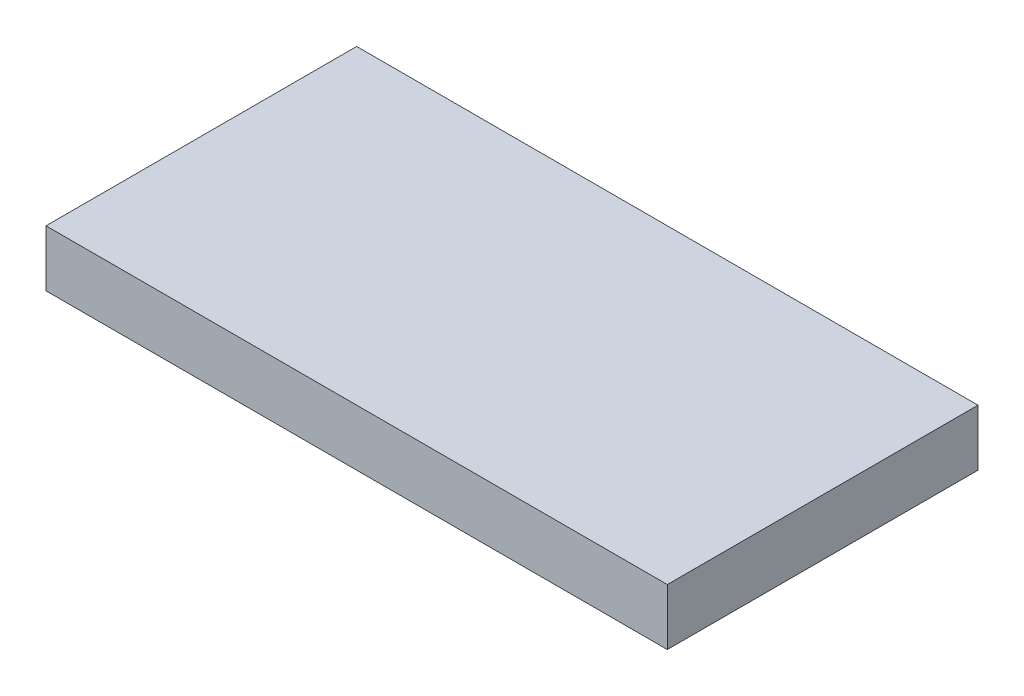
SolidWorks part; units mm, degrees
ref_plane "前视基准面" through (0, 0, 0) normal (0, 0, 1) x (1, 0, 0)
ref_plane "上视基准面" through (0, 0, 0) normal (0, 1, 0) x (1, 0, 0)
ref_plane "右视基准面" through (0, 0, 0) normal (1, 0, 0) x (0, 0, -1)
other "Configuration Table"
sketch "草图1" plane through (0, 0, 0) normal (0, 1, 0) x (1, 0, 0)
  line L0 (0, 0) -> (0, 80)
  line L1 (0, 80) -> (80, 80)
  line L2 (80, 80) -> (80, 0)
  line L3 (80, 0) -> (-80, 0)
  line L4 (-80, 0) -> (-80, 80)
  line L5 (-80, 80) -> (0, 80)
  dimension "D1" = 80
  dimension "D2" = 80
  dimension "D3" = 80
  dimension "D4" = 80
extrude "凸台-拉伸1" add sketch "草图1" along normal blind 14.5
sketch "草图3" plane through (0, 0, 0) normal (0, -1, 0) x (1, 0, 0)
  line L0 (0, 0) -> (0, -15)
  line L1 (0, -15) -> (-30, -15)
  line L2 (0, -15) -> (30, -15)
  circle A0 centre (-30, -15) radius 2
  circle A1 centre (30, -15) radius 2
  dimension "D1" = 4
  dimension "D2" = 4
extrude "切除-拉伸1" cut sketch "草图3" against normal blind 10
